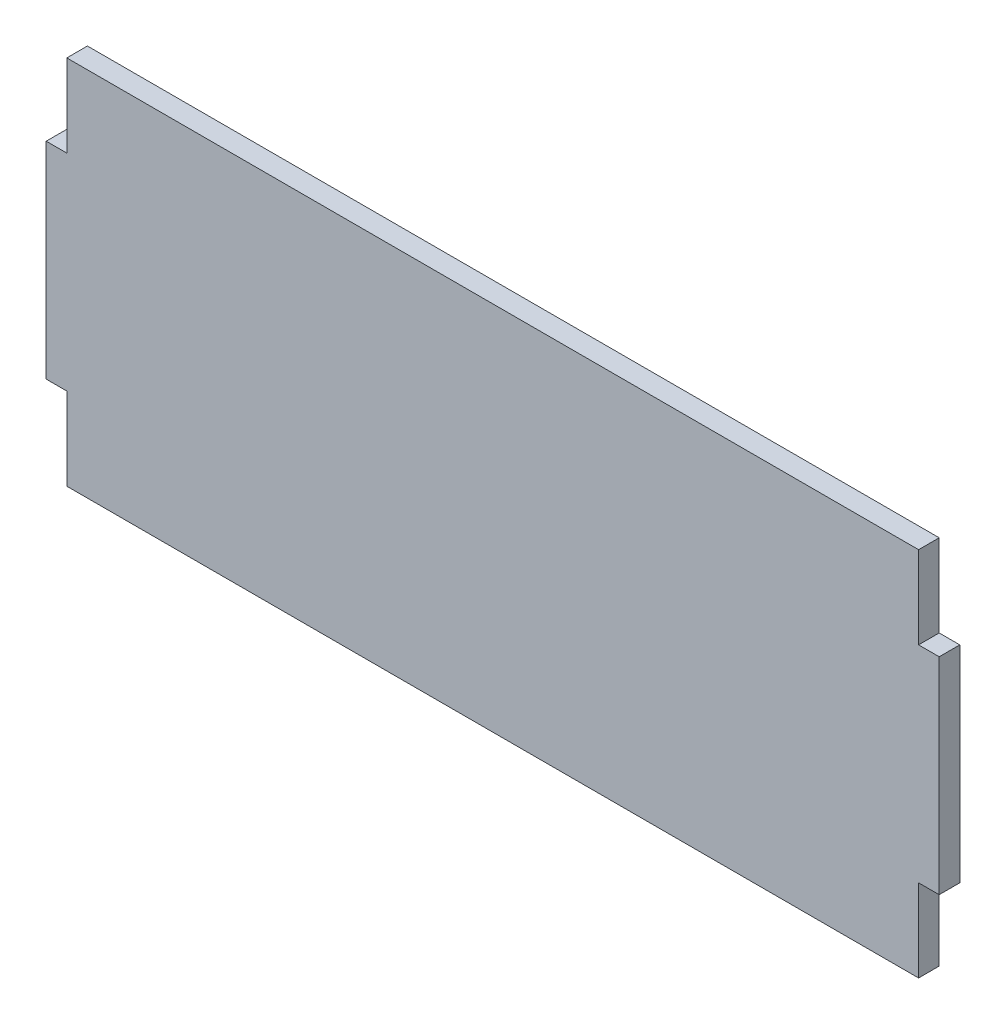
SolidWorks part; units mm, degrees
ref_plane "Front Plane" through (0, 0, 0) normal (0, 0, 1) x (1, 0, 0)
ref_plane "Top Plane" through (0, 0, 0) normal (0, 1, 0) x (1, 0, 0)
ref_plane "Right Plane" through (0, 0, 0) normal (1, 0, 0) x (0, 0, -1)
sketch "Sketch1" plane through (0, 0, 0) normal (0, 0, 1) x (1, 0, 0)
  line L0 (0, 0) -> (0, 12)
  line L1 (0, 12) -> (-3, 12)
  line L2 (-3, 12) -> (-3, 42)
  line L3 (-3, 42) -> (0, 42)
  line L4 (0, 42) -> (0, 54)
  line L5 (0, 54) -> (124, 54)
  line L6 (124, 54) -> (124, 42)
  line L7 (124, 42) -> (127, 42)
  line L8 (127, 42) -> (127, 12)
  line L9 (127, 12) -> (124, 12)
  line L10 (124, 12) -> (124, 0)
  line L11 (124, 0) -> (0, 0)
  dimension "D1" = 124
  dimension "D2" = 54
  dimension "D3" = 30
  dimension "D4" = 12
  dimension "D5" = 3
extrude "Boss-Extrude1" add sketch "Sketch1" along normal blind 3
